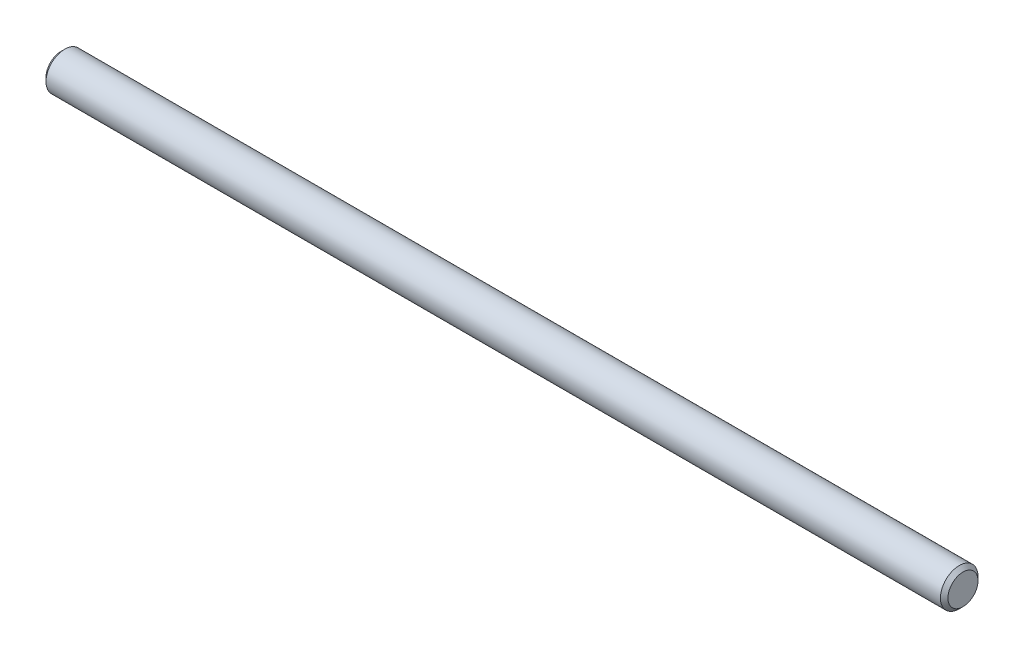
SolidWorks part; units mm, degrees
ref_plane "Front Plane" through (0, 0, 0) normal (0, 0, 1) x (1, 0, 0)
ref_plane "Top Plane" through (0, 0, 0) normal (0, 1, 0) x (1, 0, 0)
ref_plane "Right Plane" through (0, 0, 0) normal (1, 0, 0) x (0, 0, -1)
sketch "Sketch1" plane through (0, 0, 0) normal (1, 0, 0) x (0, 0, -1)
  circle A0 centre (0, 0) radius 4
extrude "Boss-Extrude1" add sketch "Sketch1" along normal mid plane 192
cosmetic thread "Cosmetic Thread1" parameters "D1"=10, "D2"=6.891
cosmetic thread "Cosmetic Thread2" parameters "D1"=10, "D2"=6.891
chamfer "Chamfer1" distance 0.8 angle 45 2 edges at (-96, 0, -4) (96, 0, -4)
